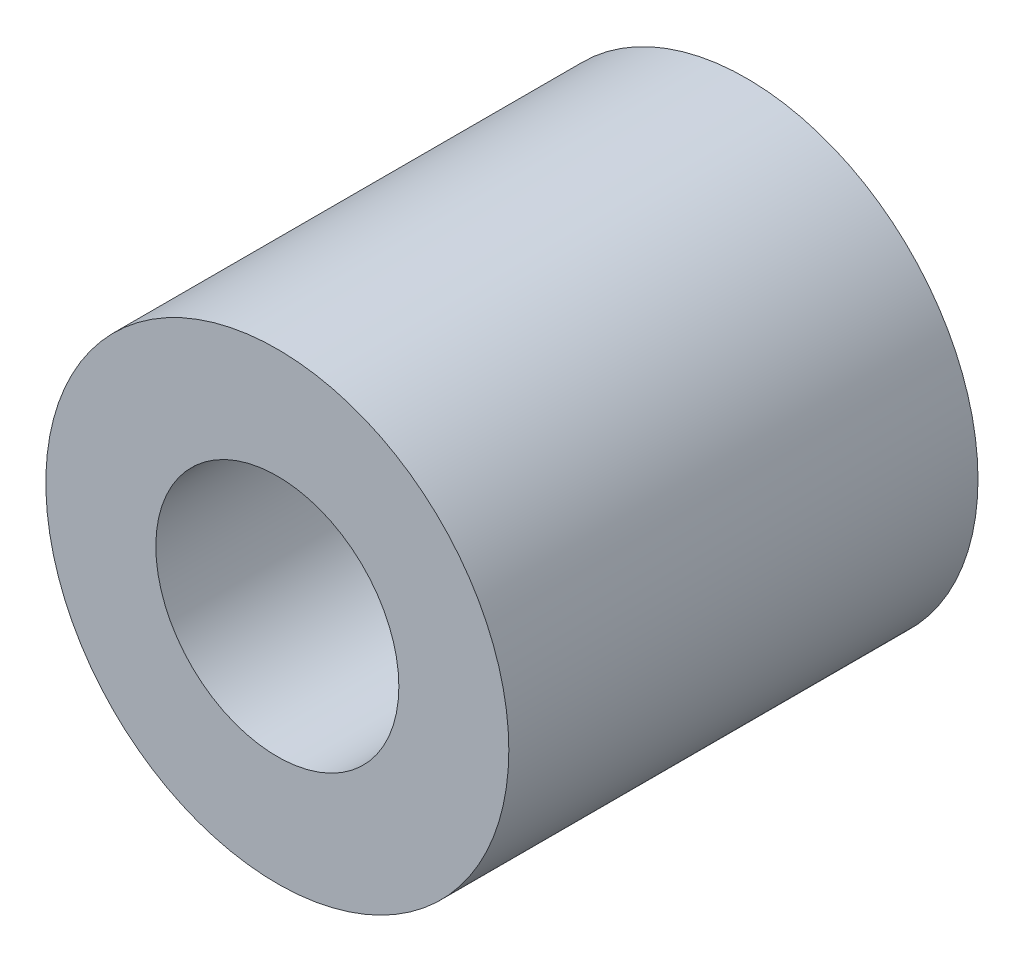
SolidWorks part; units mm, degrees
ref_plane "Front Plane" through (0, 0, 0) normal (0, 0, 1) x (1, 0, 0)
ref_plane "Top Plane" through (0, 0, 0) normal (0, 1, 0) x (1, 0, 0)
ref_plane "Right Plane" through (0, 0, 0) normal (1, 0, 0) x (0, 0, -1)
sketch "Sketch1" plane through (0, 0, 0) normal (0, 0, 1) x (1, 0, 0)
  line L0 (-1.5, 2) -> (1.5, 2)
  circle A0 centre (0, 0) radius 4.7625
  arc A1 (-1.5, 2) -> (1.5, 2) centre (0, 0) ccw
  point P6 (0, 2.5)
  point P7 (0, 2)
  dimension "D1" = 9.525
  dimension "D2" = 5
  dimension "D3" = 0.5
extrude "Boss-Extrude1" add sketch "Sketch1" along normal blind 9
sketch "Sketch2" plane through (0, 0, 9) normal (0, 0, 1) x (1, 0, 0)
  circle A0 centre (0, 0) radius 4.7625
  circle A1 centre (0, 0) radius 2.5
extrude "Boss-Extrude2" add sketch "Sketch2" along normal blind 0.652
